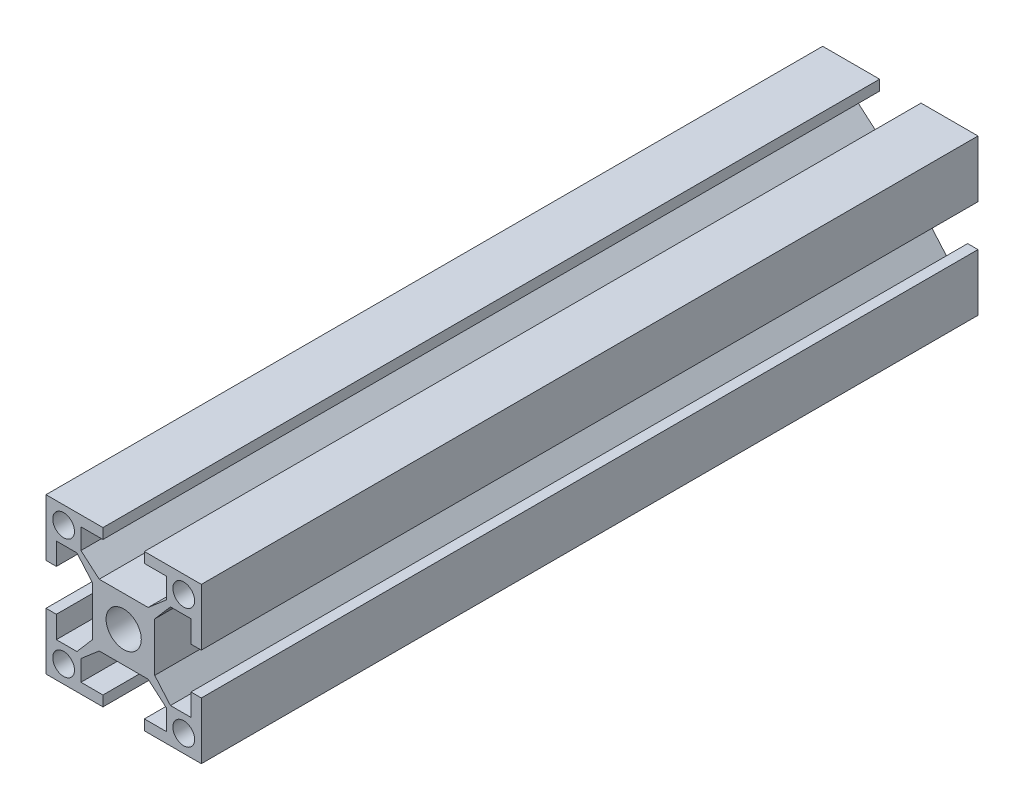
SolidWorks part; units mm, degrees
ref_plane "Front Plane" through (0, 0, 0) normal (0, 0, 1) x (1, 0, 0)
ref_plane "Top Plane" through (0, 0, 0) normal (0, 1, 0) x (1, 0, 0)
ref_plane "Right Plane" through (0, 0, 0) normal (1, 0, 0) x (0, 0, -1)
sketch "Sketch3" plane through (0, 0, 0) normal (0, 0, 1) x (1, 0, 0)
  line L51 (8.6667, -5.5) -> (6.0196, -5.5)
  line L52 (3.1508, -4) -> (0, -4)
  line L53 (-5.5, 8.6667) -> (-5.5, 6.0196)
  line L54 (10, -2.6667) -> (8.6667, -2.6667)
  line L56 (-3.1508, 4) -> (0, 4)
  line L57 (8.6667, -2.6667) -> (8.6667, -5.5)
  line L58 (4, 3.1508) -> (4, 0)
  line L59 (8.6667, 2.6667) -> (8.6667, 5.5)
  line L60 (5.5, -6.0196) -> (3.1508, -4)
  line L61 (-6.0196, 5.5) -> (-4, 3.1508)
  line L62 (-8.6667, -5.5) -> (-6.0196, -5.5)
  line L63 (-10, -10) -> (-10.0001, -2.6667)
  line L64 (6.0196, -5.5) -> (4, -3.1508)
  line L65 (-4, 3.1508) -> (-4, 0)
  line L66 (10.0001, 2.6667) -> (10, 10)
  line L67 (-2.6667, 10) -> (-2.6667, 8.6667)
  line L68 (-8.6667, 2.6667) -> (-8.6667, 5.5)
  line L69 (-6.0196, -5.5) -> (-4, -3.1508)
  line L70 (4, -3.1508) -> (4, 0)
  line L71 (-5.5, -6.0196) -> (-3.1508, -4)
  line L72 (10.0001, 2.6667) -> (8.6667, 2.6667)
  line L73 (8.6667, 5.5) -> (6.0196, 5.5)
  line L74 (6.0196, 5.5) -> (4, 3.1508)
  line L75 (2.6667, -8.6667) -> (5.5, -8.6667)
  line L76 (10, -10) -> (10, -2.6667)
  line L77 (-5.5, -8.6667) -> (-5.5, -6.0196)
  line L78 (-5.5, 6.0196) -> (-3.1508, 4)
  line L79 (5.5, 8.6667) -> (5.5, 6.0196)
  line L80 (-8.6667, -2.6667) -> (-8.6667, -5.5)
  line L81 (-2.6667, 8.6667) -> (-5.5, 8.6667)
  line L82 (2.6667, 8.6667) -> (5.5, 8.6667)
  line L83 (-2.6667, -8.6667) -> (-5.5, -8.6667)
  line L84 (-10, 2.6667) -> (-8.6667, 2.6667)
  line L85 (2.6667, -10.0001) -> (2.6667, -8.6667)
  line L86 (-2.6667, -10) -> (-2.6667, -8.6667)
  line L87 (-10.0001, -2.6667) -> (-8.6667, -2.6667)
  line L88 (2.6667, -10.0001) -> (10, -10)
  line L89 (-10, -10) -> (-2.6667, -10)
  line L90 (5.5, 6.0196) -> (3.1508, 4)
  line L91 (-3.1508, -4) -> (0, -4)
  line L92 (5.5, -8.6667) -> (5.5, -6.0196)
  line L93 (-10, 2.6667) -> (-10, 10)
  line L94 (-10, 10) -> (-2.6667, 10)
  line L95 (-8.6667, 5.5) -> (-6.0196, 5.5)
  line L96 (3.1508, 4) -> (0, 4)
  line L97 (2.6667, 10) -> (2.6667, 8.6667)
  line L98 (2.6667, 10) -> (10, 10)
  line L99 (-4, -3.1508) -> (-4, 0)
  line L100 (-10, -10) -> (10, 10) construction
  line L101 (-10, 10) -> (10, -10) construction
  circle A5 centre (7.7334, -7.7334) radius 1.4
  circle A6 centre (7.7334, 7.7334) radius 1.4
  circle A7 centre (-7.7334, 7.7334) radius 1.4
  circle A8 centre (0, 0) radius 2.2667
  circle A9 centre (-7.7334, -7.7334) radius 1.4
  point P0 (0, 0)
  point P23 (0, 0)
  point P32 (0, 0)
  point P35 (0, 0)
  point P47 (0, 0)
  point P59 (0, 0)
  point P71 (0, 0)
  point P91 (-2.6667, 10)
  point P92 (2.6667, 10)
  point P99 (0, 0)
  point P100 (0, 0)
  point P112 (0, 0)
  point P124 (0, 0)
  point P136 (0, 0)
  dimension "D12" = 4
extrude "Boss-Extrude1" add sketch "Sketch3" along normal blind 100
